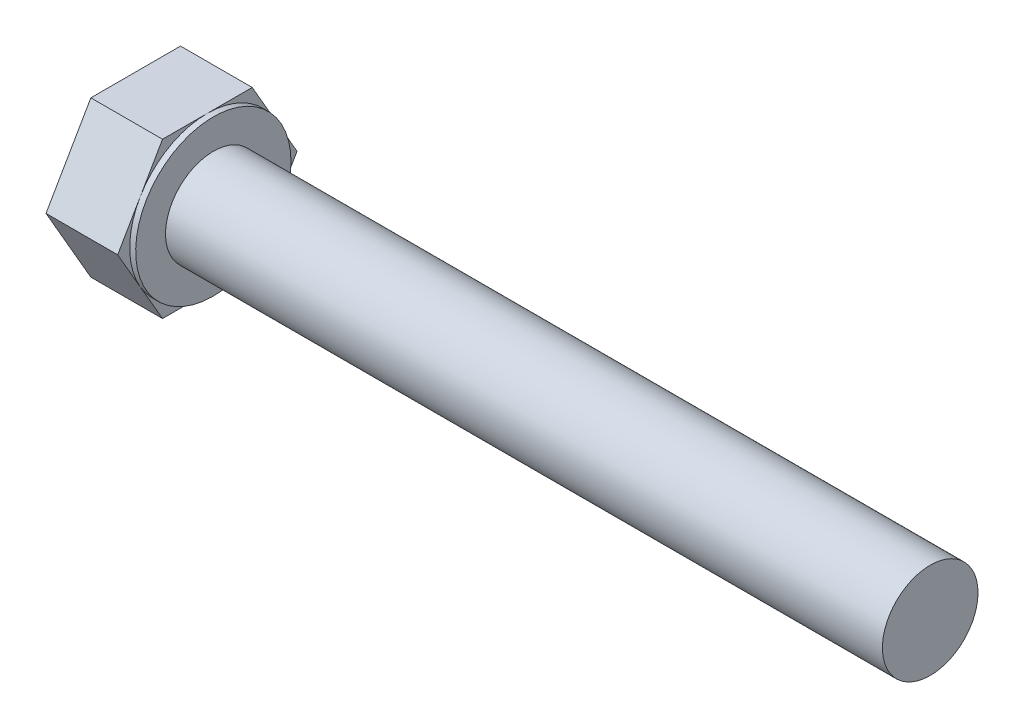
SolidWorks part; units mm, degrees
material "Plain Carbon Steel"
ref_plane "Front Plane" through (0, 0, 0) normal (0, 0, 1) x (1, 0, 0)
ref_plane "Top Plane" through (0, 0, 0) normal (0, 1, 0) x (1, 0, 0)
ref_plane "Right Plane" through (0, 0, 0) normal (1, 0, 0) x (0, 0, -1)
sketch "Sketch1" plane through (0, 0, 0) normal (1, 0, 0) x (0, 0, -1)
  line L1 (-7.5056, 0) -> (-3.7528, -6.5)
  line L2 (-3.7528, -6.5) -> (3.7528, -6.5)
  line L3 (3.7528, -6.5) -> (7.5056, 0)
  line L4 (7.5056, 0) -> (3.7528, 6.5)
  line L5 (3.7528, 6.5) -> (-3.7528, 6.5)
  line L6 (-3.7528, 6.5) -> (-7.5056, 0)
  circle A0 centre (0, 0) radius 6.5 construction
  dimension "D1" = 13
extrude "Boss-Extrude1" add sketch "Sketch1" against normal blind 6
sketch "Sketch2" plane through (0, 0, 0) normal (1, 0, 0) x (0, 0, -1)
  line L0 (3.7528, 6.5) -> (-3.7528, 6.5) construction
  circle A0 centre (0, 0) radius 6.5
extrude "Boss-Extrude2" add sketch "Sketch2" along normal blind 0.5
sketch "Sketch3" plane through (0.5, 0, 0) normal (1, 0, 0) x (0, 0, -1)
  circle A0 centre (0, 0) radius 4
  dimension "D1" = 8
extrude "Boss-Extrude3" add sketch "Sketch3" along normal blind 60
